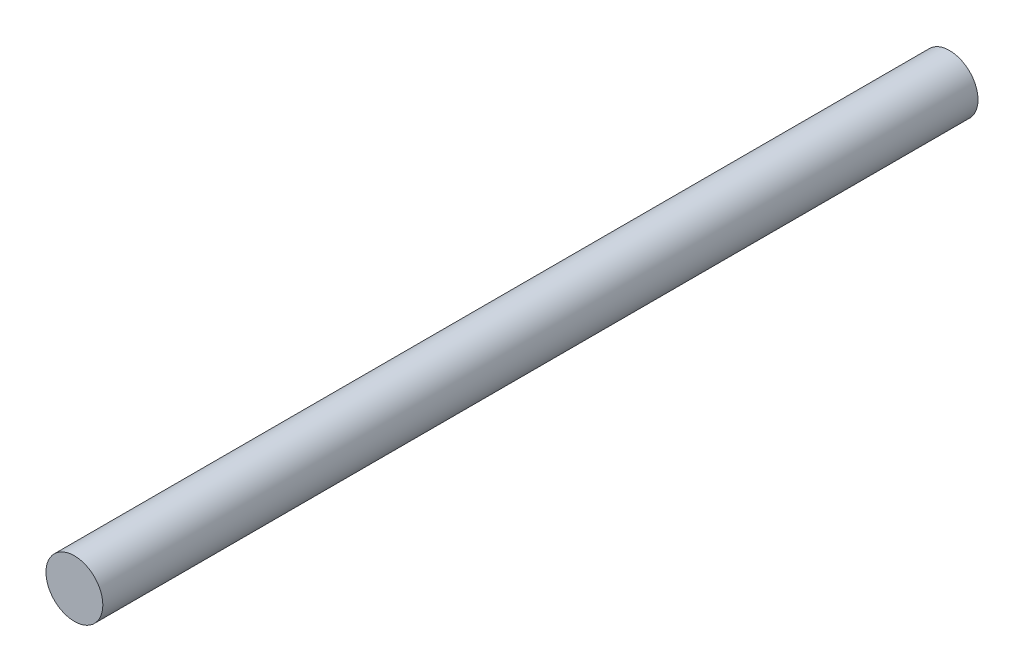
SolidWorks part; units mm, degrees
ref_plane "Front Plane" through (0, 0, 0) normal (0, 0, 1) x (1, 0, 0)
ref_plane "Top Plane" through (0, 0, 0) normal (0, 1, 0) x (1, 0, 0)
ref_plane "Right Plane" through (0, 0, 0) normal (1, 0, 0) x (0, 0, -1)
sketch "Sketch1" plane through (0, 0, 0) normal (0, 0, 1) x (1, 0, 0)
  circle A0 centre (0, 0) radius 1.651
extrude "Boss-Extrude1" add sketch "Sketch1" along normal blind 50.8
